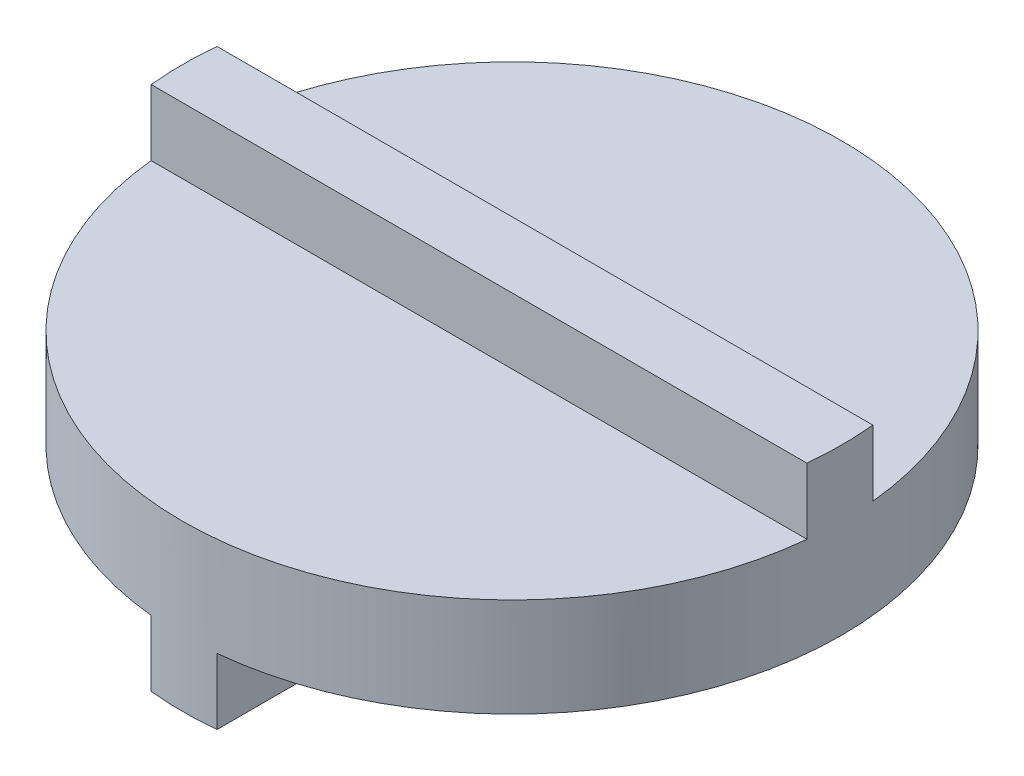
SolidWorks part; units mm, degrees
ref_plane "Front Plane" through (0, 0, 0) normal (0, 0, 1) x (1, 0, 0)
ref_plane "Top Plane" through (0, 0, 0) normal (0, 1, 0) x (1, 0, 0)
ref_plane "Right Plane" through (0, 0, 0) normal (1, 0, 0) x (0, 0, -1)
sketch "Sketch1" plane through (0, 0, 0) normal (0, 1, 0) x (1, 0, 0)
  circle A0 centre (0, 0) radius 50
  dimension "D1" = 100
extrude "Boss-Extrude1" add sketch "Sketch1" along normal blind 15
sketch "Sketch2" plane through (0, 15, 0) normal (0, 1, 0) x (1, 0, 0)
  line L0 (-49.7494, 5) -> (49.7494, 5)
  line L1 (-49.7494, -5) -> (49.7494, -5)
  line L2 (-49.7494, -5) -> (49.7494, -5) construction
  circle A0 centre (0, 0) radius 50 construction
  arc A1 (-49.7494, 5) -> (-49.7494, -5) centre (0, 0) ccw
  arc A2 (49.7494, -5) -> (49.7494, 5) centre (0, 0) ccw
  dimension "D2" = 5
  dimension "D1" = 10
extrude "Boss-Extrude2" add sketch "Sketch2" along normal blind 10
sketch "Sketch3" plane through (0, 0, 0) normal (0, -1, 0) x (1, 0, 0)
  line L0 (5, -49.7494) -> (5, 49.7494)
  line L1 (-5, 49.7494) -> (-5, -49.7494)
  line L8 (-5, 49.7494) -> (-5, -49.7494)
  line L9 (5, -49.7494) -> (5, 49.7494)
  arc A0 (5, 49.7494) -> (-5, 49.7494) centre (0, 0) ccw
  circle A1 centre (0, 0) radius 50
  arc A2 (5, 49.7494) -> (-5, 49.7494) centre (0, 0) ccw
  arc A3 (5, 49.7494) -> (-5, 49.7494) centre (0, 0) ccw
  arc A8 (5, 49.7494) -> (-5, 49.7494) centre (0, 0) ccw
  arc A9 (-5, -49.7494) -> (5, -49.7494) centre (0, 0) ccw
  arc A10 (-5, -49.7494) -> (5, -49.7494) centre (0, 0) ccw
  arc A11 (-5, -49.7494) -> (5, -49.7494) centre (0, 0) ccw
  arc A12 (-5, -49.7494) -> (5, -49.7494) centre (0, 0) ccw
  point P27 (0, 0)
  circle M8 centre (0, 0) radius 50
  dimension "D4" = 10
  dimension "D5" = 5
  dimension "D1" = 0
  dimension "D3" = 4
extrude "Boss-Extrude3" add sketch "Sketch3" along normal blind 10 contours L1 L0 M8
